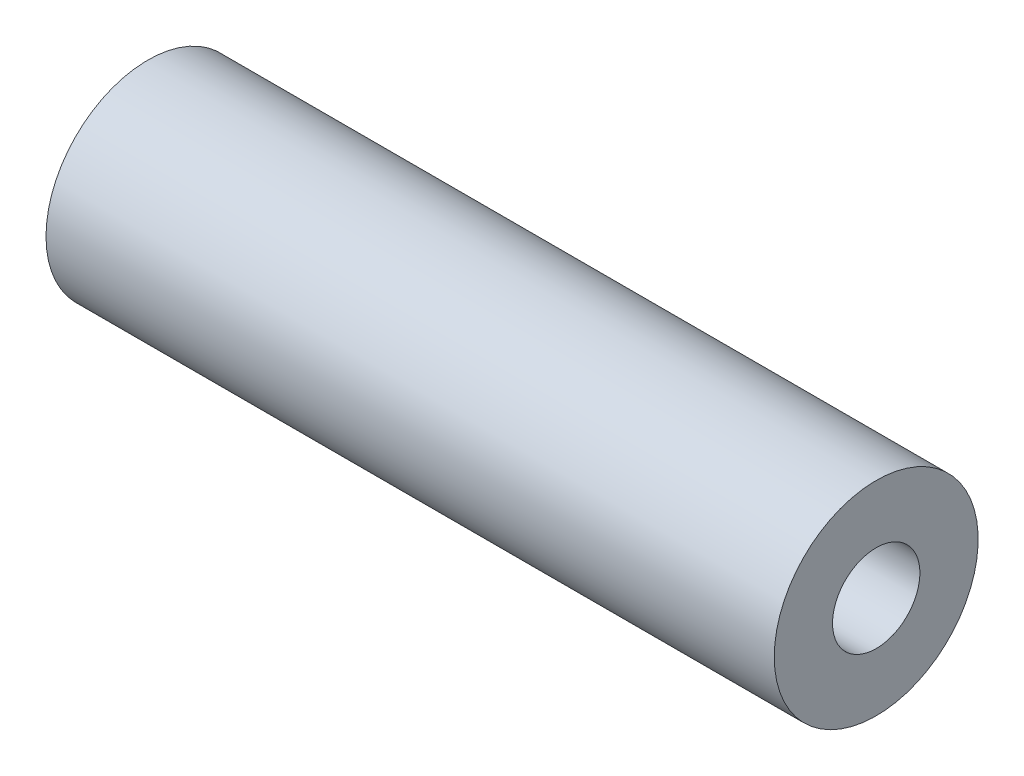
SolidWorks part; units mm, degrees
material "PVC 0.007 Plasticized"
ref_plane "Front Plane" through (0, 0, 0) normal (0, 0, 1) x (1, 0, 0)
ref_plane "Top Plane" through (0, 0, 0) normal (0, 1, 0) x (1, 0, 0)
ref_plane "Right Plane" through (0, 0, 0) normal (1, 0, 0) x (0, 0, -1)
sketch "Sketch1" plane through (0, 0, 0) normal (1, 0, 0) x (0, 0, -1)
  circle A0 centre (0, 0) radius 3.5
  circle A1 centre (0, 0) radius 1.5
  dimension "D1" = 7
  dimension "D2" = 3
extrude "Boss-Extrude1" add sketch "Sketch1" along normal mid plane 25
